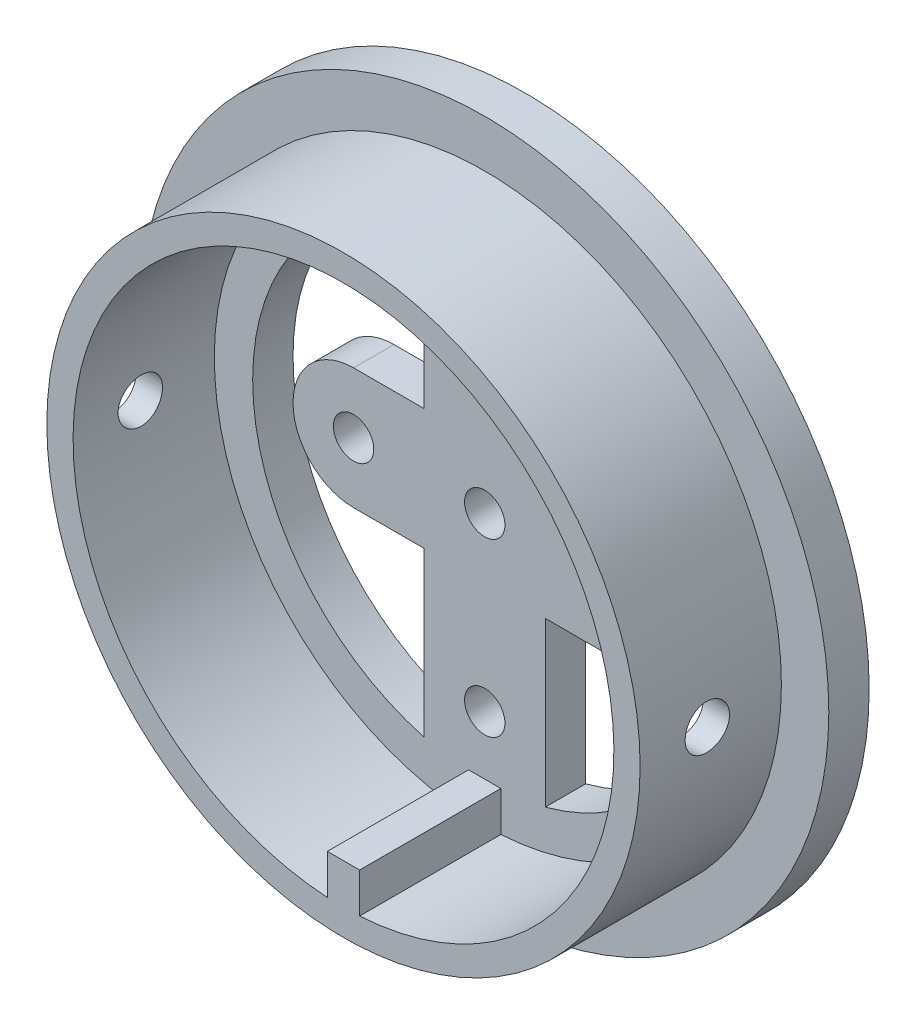
SolidWorks part; units mm, degrees
ref_plane "Front Plane" through (0, 0, 0) normal (0, 0, 1) x (1, 0, 0)
ref_plane "Top Plane" through (0, 0, 0) normal (0, 1, 0) x (1, 0, 0)
ref_plane "Right Plane" through (0, 0, 0) normal (1, 0, 0) x (0, 0, -1)
sketch "Sketch1" plane through (0, 0, 0) normal (0, 0, 1) x (1, 0, 0)
  line L0 (0, -14.7) -> (0, 14.7) construction
  circle A0 centre (0, 0) radius 14.7
  circle A1 centre (0, 0) radius 13.4
  dimension "D1" = 26.8
  dimension "D2" = 29.4
extrude "Boss-Extrude1" add sketch "Sketch1" along normal blind 7
sketch "Sketch2" plane through (0, 0, 0) normal (0, 0, 1) x (1, 0, 0)
  line L0 (0, -14.7) -> (0, 14.7) construction
  line L1 (0, -13.4) -> (0, -11.4) construction
  line L2 (-0.8, -13.4) -> (0.8, -13.4)
  line L3 (-0.8, -13.4) -> (-0.8, -11.4)
  line L4 (-0.8, -11.4) -> (0.8, -11.4)
  line L5 (0.8, -11.4) -> (0.8, -13.4)
  circle A0 centre (0, 0) radius 13.4 construction
  arc A1 (-0.8, -13.3761) -> (0.8, -13.3761) centre (0, 0) ccw construction
  point P8 (0, -13.4)
  dimension "D1" = 1.6
  dimension "D2" = 2
extrude "Boss-Extrude2" add sketch "Sketch2" along normal blind 7
sketch "Sketch3" plane through (0, 0, 0) normal (1, 0, 0) x (0, 0, -1)
  line L0 (0, 0) -> (-7, 0) construction
  line L1 (-7, 14.7) -> (-7, -14.7) construction
  circle A0 centre (-3.67, 0) radius 1.1
  dimension "D1" = 2.2
  dimension "D2" = 3.67
extrude "Cut-Extrude1" cut sketch "Sketch3" against normal through all both and the other way through all
sketch "Sketch4" plane through (0, 0, 0) normal (0, 0, 1) x (1, 0, 0)
  circle A0 centre (0, 0) radius 11.5
  circle A1 centre (0, 0) radius 17.05
  dimension "D1" = 23
  dimension "D2" = 34.1
extrude "Boss-Extrude3" add sketch "Sketch4" against normal blind 2
sketch "Sketch5" plane through (0, 0, 0) normal (0, 0, 1) x (1, 0, 0)
  line L0 (0, 11.5) -> (0, -11.5) construction
  line L1 (-9.5, 0) -> (9.5, 0) construction
  line L2 (-6.5, -3) -> (-3, -3)
  line L3 (-6.5, 3) -> (-3, 3)
  line L7 (3, -11.5) -> (3, -3)
  line L9 (0, 11.5) -> (-3, 11.5)
  line L10 (3, 3) -> (3, 11.5)
  line L11 (-3, 3) -> (-3, 11.5)
  line L12 (3, -3) -> (6.5, -3)
  line L13 (3, 3) -> (6.5, 3)
  line L14 (0, 11.5) -> (3, 11.5)
  line L15 (3, -11.5) -> (-3, -11.5)
  line L17 (-3, -11.5) -> (-3, -3)
  arc A1 (6.5, -3) -> (6.5, 3) centre (6.5, 0) ccw
  arc A2 (-6.5, 3) -> (-6.5, -3) centre (-6.5, 0) ccw
  circle A3 centre (0, 0) radius 11.5 construction
  circle A4 centre (0, 0) radius 11.5 construction
  point P0 (3, -12.5212)
  point P4 (0, 0)
  point P8 (0, 0)
  dimension "D1" = 6
  dimension "D2" = 6
  dimension "D6" = 13
extrude "Boss-Extrude4" add sketch "Sketch5" against normal blind 2
sketch "Sketch6" plane through (0, 0, 0) normal (0, 0, 1) x (1, 0, 0)
  line L0 (0, 0) -> (0, 14.7496) construction
  line L1 (0, 0) -> (18.9086, 0) construction
  circle A0 centre (0, 0) radius 1
  circle A1 centre (6.5, 0) radius 1
  circle A2 centre (-6.5, 0) radius 1
  circle A3 centre (0, 8.5) radius 1
  circle A4 centre (0, -8.5) radius 1
  dimension "D1" = 2
  dimension "D2" = 13
  dimension "D3" = 17
extrude "Cut-Extrude2" cut sketch "Sketch6" against normal up to next
equation "\"cap_height\"=7"
equation "\"D1@Boss-Extrude1\"=\"cap_height\""
equation "\"D1@Boss-Extrude2\"=\"cap_height\""
equation "\"cap_plate_height\"=2"
equation "\"D1@Boss-Extrude3\"=\"cap_plate_height\""
equation "\"D1@Boss-Extrude4\"=\"cap_plate_height\""
